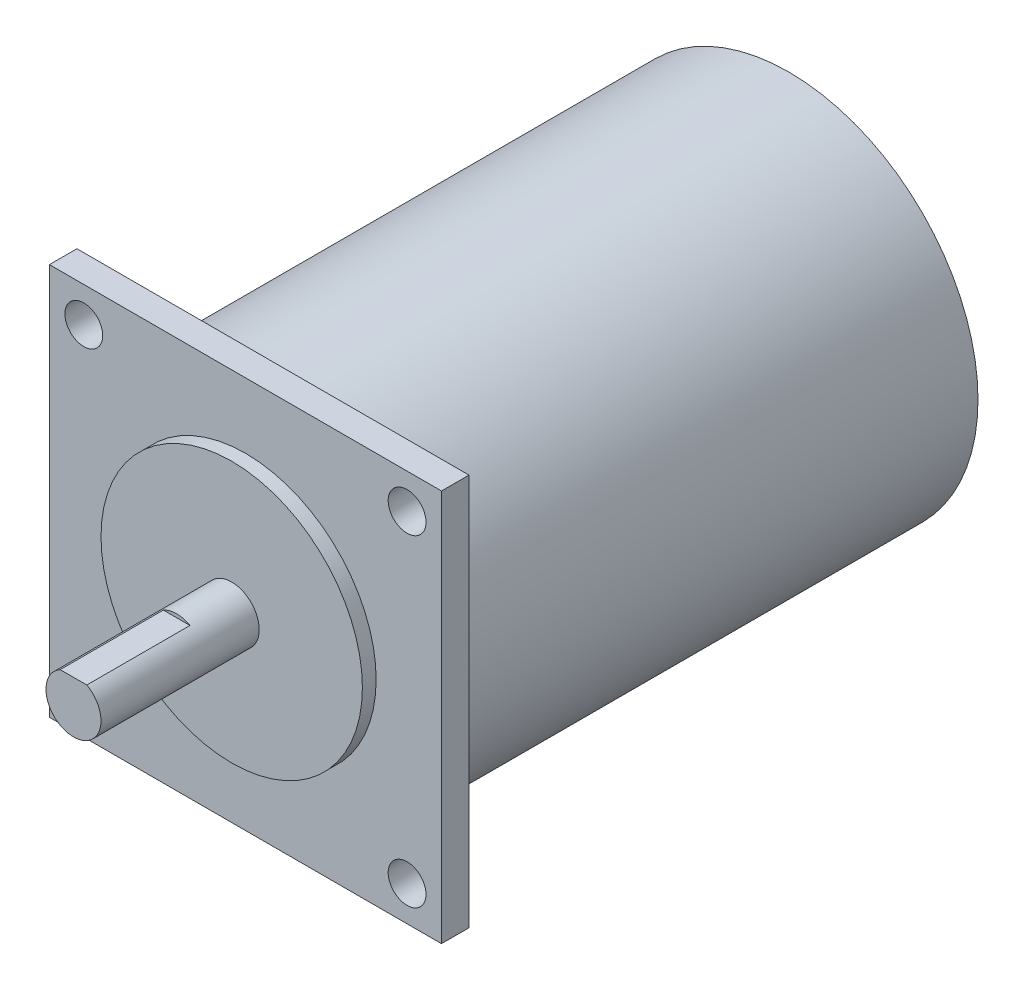
SolidWorks part; units mm, degrees
ref_plane "前视基准面" through (0, 0, 0) normal (0, 0, 1) x (1, 0, 0)
ref_plane "上视基准面" through (0, 0, 0) normal (0, 1, 0) x (1, 0, 0)
ref_plane "右视基准面" through (0, 0, 0) normal (1, 0, 0) x (0, 0, -1)
sketch "草图1" plane through (0, 0, 0) normal (0, 0, 1) x (1, 0, 0)
  line L0 (-34.6868, 8.3167) -> (22.3132, 8.3167) construction
  line L1 (-34.6868, 36.8167) -> (22.3132, 36.8167)
  line L2 (-34.6868, 36.8167) -> (-34.6868, -20.1833)
  line L3 (-34.6868, -20.1833) -> (22.3132, -20.1833)
  line L4 (22.3132, 36.8167) -> (22.3132, -20.1833)
  line L5 (-6.1868, 36.8167) -> (-6.1868, -20.1833) construction
  circle A0 centre (-29.6868, 31.7456) radius 2.75
  circle A1 centre (17.3132, 31.7456) radius 2.75
  circle A2 centre (17.3132, -15.1121) radius 2.75
  circle A3 centre (-29.6868, -15.1121) radius 2.75
  dimension "D3" = 23.5
  dimension "D4" = 5.5
  dimension "D1" = 57
  dimension "D2" = 57
extrude "凸台-拉伸1" add sketch "草图1" along normal blind 4
sketch "草图2" plane through (0, 0, 0) normal (0, 0, -1) x (-1, 0, 0)
  line L0 (-22.3132, 36.8167) -> (34.6868, -20.1833) construction
  line L1 (34.6868, 36.8167) -> (-22.3132, -20.1833) construction
  circle A0 centre (6.1868, 8.3167) radius 27.5
  dimension "D1" = 55
extrude "凸台-拉伸2" add sketch "草图2" along normal blind 75
sketch "草图3" plane through (0, 0, 4) normal (0, 0, 1) x (1, 0, 0)
  line L0 (-34.6868, 8.3167) -> (22.3132, 8.3167) construction
  line L1 (-34.6868, 36.8167) -> (-34.6868, -20.1833) construction
  line L2 (22.3132, -20.1833) -> (22.3132, 36.8167) construction
  line L3 (-6.1868, 36.8167) -> (-6.1868, -20.1833) construction
  line L4 (22.3132, 36.8167) -> (-34.6868, 36.8167) construction
  line L5 (-34.6868, -20.1833) -> (22.3132, -20.1833) construction
  circle A0 centre (-6.1868, 8.3167) radius 19
  dimension "D1" = 38
extrude "凸台-拉伸3" add sketch "草图3" along normal blind 2
sketch "草图4" plane through (0, 0, 6) normal (0, 0, 1) x (1, 0, 0)
  line L0 (-6.1868, 27.3167) -> (-6.1868, -11.1102) construction
  circle A0 centre (-6.1868, 8.3167) radius 19 construction
  circle A1 centre (-6.1868, 8.1033) radius 4
  dimension "D1" = 8
extrude "凸台-拉伸4" add sketch "草图4" along normal blind 23
ref_plane "基准面1" through (-2.1868, 0, 0) normal (1, 0, 0) x (0, 0, -1)
sketch "草图5" plane through (-2.1868, 0, 0) normal (1, 0, 0) x (0, 0, -1)
  line L1 (-29, 12.1033) -> (-29, 4.1033) construction
  line L2 (-14, 11.6033) -> (-14, 12.1033)
  line L3 (-6, 12.1033) -> (-29, 12.1033) construction
  line L4 (-14, 12.1033) -> (-29, 12.1033)
  line L5 (-29, 12.1033) -> (-29, 11.6033)
  line L6 (-29, 11.6033) -> (-14, 11.6033)
  dimension "D1" = 15
  dimension "D2" = 0.5
extrude "切除-拉伸1" cut sketch "草图5" against normal blind 23
